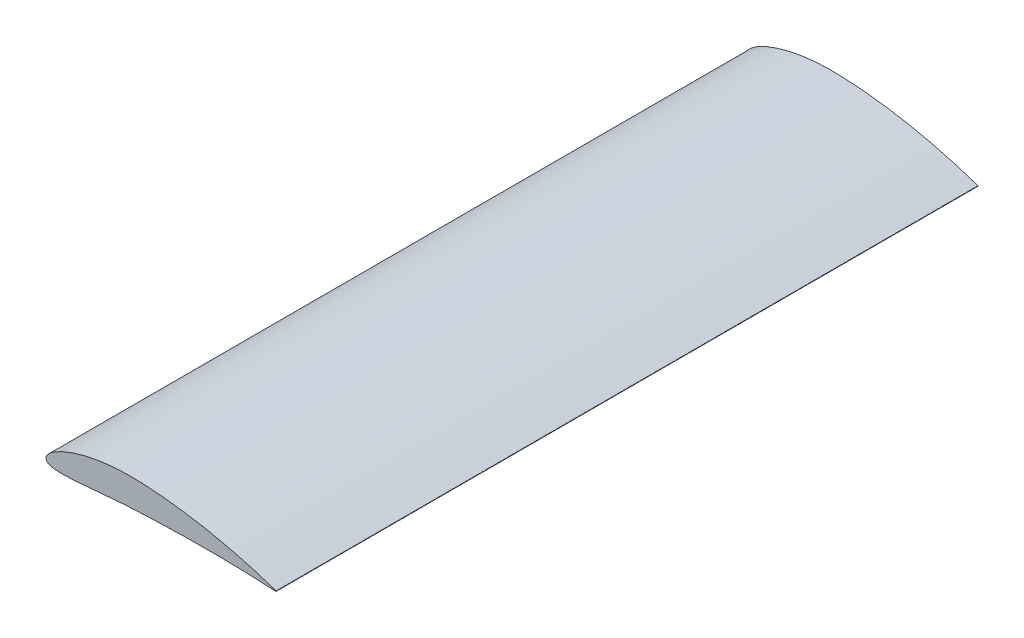
SolidWorks part; units mm, degrees
ref_plane "Front Plane" through (0, 0, 0) normal (0, 0, 1) x (1, 0, 0)
ref_plane "Top Plane" through (0, 0, 0) normal (0, 1, 0) x (1, 0, 0)
ref_plane "Right Plane" through (0, 0, 0) normal (1, 0, 0) x (0, 0, -1)
curve "Curve1"
  spline degree 3 poles (25.4063, 0.0315, 0) (25.3837, 0.0393, 0) (25.2937, 0.0703, 0) (25.0921, 0.1399, 0) (24.7577, 0.2522, 0) (24.2942, 0.405, 0) (23.7055, 0.5921, 0) (22.997, 0.8077, 0) (22.1758, 1.0451, 0) (21.2496, 1.2966, 0) (20.228, 1.5548, 0) (19.121, 1.8116, 0) (17.9406, 2.0603, 0) (16.6991, 2.2931, 0) (15.4099, 2.5029, 0) (14.087, 2.6845, 0) (12.7455, 2.832, 0) (11.3997, 2.9406, 0) (10.0556, 3.012, 0) (8.7276, 3.0204, 0) (7.4344, 2.9555, 0) (6.2027, 2.8238, 0) (5.0487, 2.6331, 0) (3.9878, 2.3917, 0) (3.0332, 2.1114, 0) (2.1961, 1.8047, 0) (1.4854, 1.4841, 0) (0.9079, 1.1619, 0) (0.4662, 0.8495, 0) (0.1626, 0.5537, 0) (-0.0122, 0.2735, 0) (-0.028, -0.0084, 0) (0.1391, -0.2343, 0) (0.4322, -0.3758, 0) (0.835, -0.4687, 0) (1.354, -0.5173, 0) (1.984, -0.5271, 0) (2.719, -0.502, 0) (3.5507, -0.4482, 0) (4.4705, -0.3722, 0) (5.4695, -0.2826, 0) (6.5387, -0.187, 0) (7.6688, -0.0938, 0) (8.8505, -0.0116, 0) (10.0833, 0.0504, 0) (11.3564, 0.0941, 0) (12.6563, 0.1392, 0) (13.9604, 0.1753, 0) (15.2542, 0.2014, 0) (16.5239, 0.216, 0) (17.7555, 0.2186, 0) (18.9353, 0.21, 0) (20.05, 0.192, 0) (21.0867, 0.1653, 0) (22.0333, 0.1345, 0) (22.8789, 0.1002, 0) (23.6118, 0.0674, 0) (24.228, 0.0327, 0) (24.706, 0.0159, 0) (25.0741, -0.0269, 0) (25.2565, -0.0004, 0) (25.3969, -0.052, 0) (25.3993, -0.0123, 0) (25.4, 0, 0) knots 0 0 0 0 0.001372 0.005465 0.012235 0.021602 0.033461 0.047671 0.064081 0.082496 0.102719 0.124527 0.147676 0.171913 0.196978 0.222597 0.248497 0.274385 0.300041 0.32569 0.350525 0.37428 0.396711 0.417577 0.436654 0.453744 0.46868 0.481329 0.491631 0.499616 0.505546 0.510185 0.514824 0.520702 0.528516 0.538466 0.550543 0.564643 0.580638 0.598345 0.617584 0.638174 0.659922 0.682632 0.706121 0.730727 0.7557 0.780732 0.805564 0.829932 0.85357 0.876213 0.89761 0.917519 0.935698 0.951943 0.966047 0.97784 0.987174 0.993932 0.998018 0.999386 1 1 1 1
ref_plane "Ground" through (0, 50, 0) normal (0, 1, 0) x (1, 0, 0)
sketch "Sketch1" plane through (0, 0, 0) normal (0, 0, 1) x (1, 0, 0)
  line L0 (399.9016, -56.6273) -> (400, -56.1315)
  line L1 (400, -56.1315) -> (0, -56.1315) construction
  line L2 (0, -56.1315) -> (0, -58.6766) construction
  line L3 (0, -56.1315) -> (33.1119, -56.1315) construction
  line L4 (0, 50) -> (0, -115.3886) construction
  line L5 (244.1729, 50) -> (-244.1729, 50) construction
  line L6 (120.4, -56.1315) -> (116.5924, -10) construction
  line L7 (-44.4989, -10) -> (307.508, -10) construction
  spline S1 degree 3 poles (400, -56.1315) (399.6439, -56.01) (398.2252, -55.5262) (395.0494, -54.4413) (389.7834, -52.6913) (382.4827, -50.3092) (373.21, -47.3936) (362.0519, -44.0359) (349.1184, -40.342) (334.534, -36.4293) (318.4458, -32.4165) (301.0159, -28.4316) (282.4307, -24.5755) (262.8848, -20.9743) (242.5889, -17.7351) (221.7662, -14.9428) (200.6508, -12.6886) (179.4693, -11.0453) (158.3174, -9.9888) (137.4224, -9.9218) (117.0768, -11.0062) (97.7026, -13.1385) (79.5557, -16.1958) (62.8746, -20.0462) (47.8681, -24.5037) (34.711, -29.37) (23.5446, -34.4495) (14.474, -39.5475) (7.5391, -44.4847) (2.7768, -49.154) (0.0409, -53.5706) (-0.1945, -58.008) (2.4464, -61.5541) (7.0638, -63.7654) (13.4071, -65.2069) (21.576, -65.9474) (31.4893, -66.0698) (43.0523, -65.6389) (56.1353, -64.7525) (70.6041, -63.511) (86.3185, -62.0516) (103.1371, -60.4954) (120.9147, -58.9731) (139.5039, -57.6216) (158.8992, -56.5864) (178.9277, -55.8354) (199.3786, -55.0619) (219.8967, -54.4309) (240.2531, -53.9568) (260.2306, -53.6642) (279.6093, -53.5627) (298.1732, -53.6409) (315.7128, -53.8686) (332.026, -54.2377) (346.9212, -54.6757) (360.2284, -55.1752) (371.7614, -55.6544) (381.4587, -56.1708) (388.9808, -56.412) (394.7752, -57.0663) (397.6444, -56.6402) (399.8562, -57.446) (399.8909, -56.8211) (399.9016, -56.6273) knots 0 0 0 0 0.001372 0.005465 0.012235 0.021602 0.033461 0.047671 0.064081 0.082496 0.102719 0.124527 0.147676 0.171913 0.196978 0.222597 0.248497 0.274385 0.300041 0.32569 0.350525 0.37428 0.396711 0.417577 0.436654 0.453744 0.46868 0.481329 0.491631 0.499616 0.505546 0.510185 0.514824 0.520702 0.528516 0.538466 0.550543 0.564643 0.580638 0.598345 0.617584 0.638174 0.659922 0.682632 0.706121 0.730727 0.7557 0.780732 0.805564 0.829932 0.85357 0.876213 0.89761 0.917519 0.935698 0.951943 0.966047 0.97784 0.987174 0.993932 0.998018 0.999386 1 1 1 1
  point P2 (120.4, -56.1315)
  dimension "D1" = 400
  dimension "D2" = 0
  dimension "D4" = 120.4
  dimension "D3" = 10
ref_plane "Plane2" through (0, 0, 75) normal (0, 0, 1) x (1, 0, 0)
ref_plane "Plane3" through (0, 0, 405) normal (0, 0, 1) x (1, 0, 0)
ref_plane "Plane4" through (0, 0, 680) normal (0, 0, 1) x (1, 0, 0)
sketch "Sketch3" plane through (0, 0, 75) normal (0, 0, 1) x (1, 0, 0)
  line L0 (399.9016, -56.6273) -> (400, -56.1315) construction
  line L1 (399.9016, -56.6273) -> (400, -56.1315)
  spline S0 degree 3 poles (385.3519, -1055.9885) (590.8884, -117.467) (493.2691, -87.9956) (395.0494, -54.4413) (389.7834, -52.6913) (382.4827, -50.3092) (373.21, -47.3936) (362.0519, -44.0359) (349.1184, -40.342) (334.534, -36.4293) (318.4458, -32.4165) (301.0159, -28.4316) (282.4307, -24.5755) (262.8848, -20.9743) (242.5889, -17.7351) (221.7662, -14.9428) (200.6508, -12.6886) (179.4693, -11.0453) (158.3174, -9.9888) (137.4224, -9.9218) (117.0768, -11.0062) (97.7026, -13.1385) (79.5557, -16.1958) (62.8746, -20.0462) (47.8681, -24.5037) (34.711, -29.37) (23.5446, -34.4495) (14.474, -39.5475) (7.5391, -44.4847) (2.7768, -49.154) (0.0409, -53.5706) (-0.1945, -58.008) (2.4464, -61.5541) (7.0638, -63.7654) (13.4071, -65.2069) (21.576, -65.9474) (31.4893, -66.0698) (43.0523, -65.6389) (56.1353, -64.7525) (70.6041, -63.511) (86.3185, -62.0516) (103.1371, -60.4954) (120.9147, -58.9731) (139.5039, -57.6216) (158.8992, -56.5864) (178.9277, -55.8354) (199.3786, -55.0619) (219.8967, -54.4309) (240.2531, -53.9568) (260.2306, -53.6642) (279.6093, -53.5627) (298.1732, -53.6409) (315.7128, -53.8686) (332.026, -54.2377) (346.9212, -54.6757) (360.2284, -55.1752) (371.7614, -55.6544) (381.4587, -56.1708) (388.9808, -56.412) (394.7752, -57.0663) (397.6444, -56.6402) (404.5727, -59.1646) (371.0225, -10.7821) (1018.233, -842.2365) knots -0.366161 -0.366161 -0.366161 -0.366161 0.001372 0.005465 0.012235 0.021602 0.033461 0.047671 0.064081 0.082496 0.102719 0.124527 0.147676 0.171913 0.196978 0.222597 0.248497 0.274385 0.300041 0.32569 0.350525 0.37428 0.396711 0.417577 0.436654 0.453744 0.46868 0.481329 0.491631 0.499616 0.505546 0.510185 0.514824 0.520702 0.528516 0.538466 0.550543 0.564643 0.580638 0.598345 0.617584 0.638174 0.659922 0.682632 0.706121 0.730727 0.7557 0.780732 0.805564 0.829932 0.85357 0.876213 0.89761 0.917519 0.935698 0.951943 0.966047 0.97784 0.987174 0.993932 0.998018 0.999386 1.012941 1.012941 1.012941 1.012941 only from (400, -56.1315) to (399.9016, -56.6273) construction
  spline S1 degree 3 poles (400, -56.1315) (399.6439, -56.01) (398.2252, -55.5262) (395.0494, -54.4413) (389.7834, -52.6913) (382.4827, -50.3092) (373.21, -47.3936) (362.0519, -44.0359) (349.1184, -40.342) (334.534, -36.4293) (318.4458, -32.4165) (301.0159, -28.4316) (282.4307, -24.5755) (262.8848, -20.9743) (242.5889, -17.7351) (221.7662, -14.9428) (200.6508, -12.6886) (179.4693, -11.0453) (158.3174, -9.9888) (137.4224, -9.9218) (117.0768, -11.0062) (97.7026, -13.1385) (79.5557, -16.1958) (62.8746, -20.0462) (47.8681, -24.5037) (34.711, -29.37) (23.5446, -34.4495) (14.474, -39.5475) (7.5391, -44.4847) (2.7768, -49.154) (0.0409, -53.5706) (-0.1945, -58.008) (2.4464, -61.5541) (7.0638, -63.7654) (13.4071, -65.2069) (21.576, -65.9474) (31.4893, -66.0698) (43.0523, -65.6389) (56.1353, -64.7525) (70.6041, -63.511) (86.3185, -62.0516) (103.1371, -60.4954) (120.9147, -58.9731) (139.5039, -57.6216) (158.8992, -56.5864) (178.9277, -55.8354) (199.3786, -55.0619) (219.8967, -54.4309) (240.2531, -53.9568) (260.2306, -53.6642) (279.6093, -53.5627) (298.1732, -53.6409) (315.7128, -53.8686) (332.026, -54.2377) (346.9212, -54.6757) (360.2284, -55.1752) (371.7614, -55.6544) (381.4587, -56.1708) (388.9808, -56.412) (394.7752, -57.0663) (397.6444, -56.6402) (399.8562, -57.446) (399.8909, -56.8211) (399.9016, -56.6273) knots 0 0 0 0 0.001372 0.005465 0.012235 0.021602 0.033461 0.047671 0.064081 0.082496 0.102719 0.124527 0.147676 0.171913 0.196978 0.222597 0.248497 0.274385 0.300041 0.32569 0.350525 0.37428 0.396711 0.417577 0.436654 0.453744 0.46868 0.481329 0.491631 0.499616 0.505546 0.510185 0.514824 0.520702 0.528516 0.538466 0.550543 0.564643 0.580638 0.598345 0.617584 0.638174 0.659922 0.682632 0.706121 0.730727 0.7557 0.780732 0.805564 0.829932 0.85357 0.876213 0.89761 0.917519 0.935698 0.951943 0.966047 0.97784 0.987174 0.993932 0.998018 0.999386 1 1 1 1
  point P2 (0, 0)
sketch "Sketch4" plane through (0, 0, 405) normal (0, 0, 1) x (1, 0, 0)
  line L0 (295.4423, -52.0945) -> (0, 0) construction
  line L1 (295.3051, -52.4479) -> (295.4423, -52.0945)
  line L2 (0, 0) -> (21.2699, 120.6274) construction
  line L3 (0, 0) -> (22.2171, 0) construction
  spline S1 degree 3 poles (295.4423, -52.0945) (295.1951, -51.9584) (294.2103, -51.4162) (292.0059, -50.2013) (288.3443, -48.2229) (283.2622, -45.5127) (276.793, -42.1516) (268.989, -38.2184) (259.9173, -33.8057) (249.6547, -29.0163) (238.2945, -23.9571) (225.9396, -18.7439) (212.7147, -13.4753) (198.7469, -8.2698) (184.1782, -3.234) (169.1621, 1.5402) (153.8597, 5.9552) (138.4289, 9.9275) (122.9436, 13.4626) (107.5192, 16.2333) (92.3506, 18.0821) (77.7629, 19.0304) (63.9613, 19.1357) (51.1392, 18.4643) (39.4747, 17.1263) (29.1231, 15.2455) (20.2139, 12.948) (12.8504, 10.364) (7.0853, 7.6205) (2.9597, 4.792) (0.3637, 1.8861) (-0.3881, -1.3607) (1.1007, -4.3238) (4.2232, -6.5585) (8.7206, -8.4493) (14.6577, -10.0601) (21.9638, -11.4415) (30.5605, -12.6292) (40.3391, -13.6784) (51.1875, -14.6458) (62.9843, -15.6144) (75.6093, -16.6554) (88.9382, -17.8463) (102.8443, -19.2691) (117.3046, -21.0304) (132.1956, -23.0842) (147.4015, -25.1763) (162.6385, -27.3824) (177.7355, -29.6834) (192.5291, -32.0691) (206.8556, -34.5179) (220.5568, -36.9934) (233.482, -39.4458) (245.483, -41.843) (256.4276, -44.1064) (266.1913, -46.2084) (274.6473, -48.0644) (281.7425, -49.7088) (287.2669, -50.8666) (291.4615, -52.1045) (293.6362, -52.1634) (295.1649, -53.0467) (295.2719, -52.5896) (295.3051, -52.4479) knots 0 0 0 0 0.001372 0.005465 0.012235 0.021602 0.033461 0.047671 0.064081 0.082496 0.102719 0.124527 0.147676 0.171913 0.196978 0.222597 0.248497 0.274385 0.300041 0.32569 0.350525 0.37428 0.396711 0.417577 0.436654 0.453744 0.46868 0.481329 0.491631 0.499616 0.505546 0.510185 0.514824 0.520702 0.528516 0.538466 0.550543 0.564643 0.580638 0.598345 0.617584 0.638174 0.659922 0.682632 0.706121 0.730727 0.7557 0.780732 0.805564 0.829932 0.85357 0.876213 0.89761 0.917519 0.935698 0.951943 0.966047 0.97784 0.987174 0.993932 0.998018 0.999386 1 1 1 1
  dimension "D1" = 10
  dimension "D2" = 300
sketch "Sketch6" plane through (0, 0, 680) normal (0, 0, 1) x (1, 0, 0)
  line L0 (299.7305, -10.839) -> (299.8172, -10.4698)
  line L1 (299.8172, -10.4698) -> (0, 0) construction
  line L2 (0, 0) -> (0.2404, 6.883) construction
  line L3 (0, 0) -> (23.729, 0) construction
  spline S1 degree 3 poles (299.8172, -10.4698) (299.5535, -10.3695) (298.5028, -9.9697) (296.1508, -9.0734) (292.2495, -7.6239) (286.8397, -5.6473) (279.9657, -3.2192) (271.6901, -0.4104) (262.0926, 2.6968) (251.2634, 6.0113) (239.3096, 9.4402) (226.3494, 12.8832) (212.52, 16.26) (197.9637, 19.4709) (182.8359, 22.4301) (167.3014, 25.068) (151.5335, 27.3103) (135.7001, 29.0964) (119.8735, 30.442) (104.2135, 31.0391) (88.9353, 30.7589) (74.3576, 29.6677) (60.6757, 27.8512) (48.0718, 25.4018) (36.707, 22.4535) (26.7179, 19.1503) (18.2152, 15.6353) (11.283, 12.0515) (5.9557, 8.5324) (2.264, 5.1572) (0.0977, 1.9184) (-0.1949, -1.4014) (1.6918, -4.1286) (5.0948, -5.9069) (9.8117, -7.1534) (15.9152, -7.9222) (23.3424, -8.2734) (32.0207, -8.2531) (41.8502, -7.9312) (52.7277, -7.3793) (64.5445, -6.6968) (77.1915, -5.9705) (90.5564, -5.2948) (104.5252, -4.7684) (119.0899, -4.5001) (134.1218, -4.4615) (149.4709, -4.417) (164.8666, -4.4811) (180.1369, -4.6585) (195.1186, -4.9621) (209.6465, -5.3933) (223.5588, -5.9378) (236.6996, -6.5675) (248.9174, -7.2712) (260.0705, -7.9894) (270.0318, -8.7121) (278.6637, -9.3732) (285.9187, -10.014) (291.5505, -10.3917) (295.8766, -11.0338) (298.0383, -10.7895) (299.675, -11.4514) (299.7174, -10.9839) (299.7305, -10.839) knots 0 0 0 0 0.001372 0.005465 0.012235 0.021602 0.033461 0.047671 0.064081 0.082496 0.102719 0.124527 0.147676 0.171913 0.196978 0.222597 0.248497 0.274385 0.300041 0.32569 0.350525 0.37428 0.396711 0.417577 0.436654 0.453744 0.46868 0.481329 0.491631 0.499616 0.505546 0.510185 0.514824 0.520702 0.528516 0.538466 0.550543 0.564643 0.580638 0.598345 0.617584 0.638174 0.659922 0.682632 0.706121 0.730727 0.7557 0.780732 0.805564 0.829932 0.85357 0.876213 0.89761 0.917519 0.935698 0.951943 0.966047 0.97784 0.987174 0.993932 0.998018 0.999386 1 1 1 1
  dimension "D1" = 2
  dimension "D2" = 300
ref_plane "Plane5" through (0, 0, 590) normal (0, 0, 1) x (1, 0, 0)
sketch "Sketch7" plane through (0, 0, 590) normal (0, 0, 1) x (1, 0, 0)
  line L0 (299.7305, -10.839) -> (299.8172, -10.4698) construction
  line L1 (299.7305, -10.839) -> (299.8172, -10.4698)
  spline S0 degree 3 poles (-87.8025, -1963.6829) (498.7146, -80.5328) (397.1503, -47.5635) (296.1508, -9.0734) (292.2495, -7.6239) (286.8397, -5.6473) (279.9657, -3.2192) (271.6901, -0.4104) (262.0926, 2.6968) (251.2634, 6.0113) (239.3096, 9.4402) (226.3494, 12.8832) (212.52, 16.26) (197.9637, 19.4709) (182.8359, 22.4301) (167.3014, 25.068) (151.5335, 27.3103) (135.7001, 29.0964) (119.8735, 30.442) (104.2135, 31.0391) (88.9353, 30.7589) (74.3576, 29.6677) (60.6757, 27.8512) (48.0718, 25.4018) (36.707, 22.4535) (26.7179, 19.1503) (18.2152, 15.6353) (11.283, 12.0515) (5.9557, 8.5324) (2.264, 5.1572) (0.0977, 1.9184) (-0.1949, -1.4014) (1.6918, -4.1286) (5.0948, -5.9069) (9.8117, -7.1534) (15.9152, -7.9222) (23.3424, -8.2734) (32.0207, -8.2531) (41.8502, -7.9312) (52.7277, -7.3793) (64.5445, -6.6968) (77.1915, -5.9705) (90.5564, -5.2948) (104.5252, -4.7684) (119.0899, -4.5001) (134.1218, -4.4615) (149.4709, -4.417) (164.8666, -4.4811) (180.1369, -4.6585) (195.1186, -4.9621) (209.6465, -5.3933) (223.5588, -5.9378) (236.6996, -6.5675) (248.9174, -7.2712) (260.0705, -7.9894) (270.0318, -8.7121) (278.6637, -9.3732) (285.9187, -10.014) (291.5505, -10.3917) (295.8766, -11.0338) (298.0383, -10.7895) (304.5078, -13.4059) (260.2474, 53.3734) (1474.4582, -1628.662) knots -0.513155 -0.513155 -0.513155 -0.513155 0.001372 0.005465 0.012235 0.021602 0.033461 0.047671 0.064081 0.082496 0.102719 0.124527 0.147676 0.171913 0.196978 0.222597 0.248497 0.274385 0.300041 0.32569 0.350525 0.37428 0.396711 0.417577 0.436654 0.453744 0.46868 0.481329 0.491631 0.499616 0.505546 0.510185 0.514824 0.520702 0.528516 0.538466 0.550543 0.564643 0.580638 0.598345 0.617584 0.638174 0.659922 0.682632 0.706121 0.730727 0.7557 0.780732 0.805564 0.829932 0.85357 0.876213 0.89761 0.917519 0.935698 0.951943 0.966047 0.97784 0.987174 0.993932 0.998018 0.999386 1.017919 1.017919 1.017919 1.017919 only from (299.8172, -10.4698) to (299.7305, -10.839) construction
  spline S1 degree 3 poles (299.8172, -10.4698) (299.5535, -10.3695) (298.5028, -9.9697) (296.1508, -9.0734) (292.2495, -7.6239) (286.8397, -5.6473) (279.9657, -3.2192) (271.6901, -0.4104) (262.0926, 2.6968) (251.2634, 6.0113) (239.3096, 9.4402) (226.3494, 12.8832) (212.52, 16.26) (197.9637, 19.4709) (182.8359, 22.4301) (167.3014, 25.068) (151.5335, 27.3103) (135.7001, 29.0964) (119.8735, 30.442) (104.2135, 31.0391) (88.9353, 30.7589) (74.3576, 29.6677) (60.6757, 27.8512) (48.0718, 25.4018) (36.707, 22.4535) (26.7179, 19.1503) (18.2152, 15.6353) (11.283, 12.0515) (5.9557, 8.5324) (2.264, 5.1572) (0.0977, 1.9184) (-0.1949, -1.4014) (1.6918, -4.1286) (5.0948, -5.9069) (9.8117, -7.1534) (15.9152, -7.9222) (23.3424, -8.2734) (32.0207, -8.2531) (41.8502, -7.9312) (52.7277, -7.3793) (64.5445, -6.6968) (77.1915, -5.9705) (90.5564, -5.2948) (104.5252, -4.7684) (119.0899, -4.5001) (134.1218, -4.4615) (149.4709, -4.417) (164.8666, -4.4811) (180.1369, -4.6585) (195.1186, -4.9621) (209.6465, -5.3933) (223.5588, -5.9378) (236.6996, -6.5675) (248.9174, -7.2712) (260.0705, -7.9894) (270.0318, -8.7121) (278.6637, -9.3732) (285.9187, -10.014) (291.5505, -10.3917) (295.8766, -11.0338) (298.0383, -10.7895) (299.675, -11.4514) (299.7174, -10.9839) (299.7305, -10.839) knots 0 0 0 0 0.001372 0.005465 0.012235 0.021602 0.033461 0.047671 0.064081 0.082496 0.102719 0.124527 0.147676 0.171913 0.196978 0.222597 0.248497 0.274385 0.300041 0.32569 0.350525 0.37428 0.396711 0.417577 0.436654 0.453744 0.46868 0.481329 0.491631 0.499616 0.505546 0.510185 0.514824 0.520702 0.528516 0.538466 0.550543 0.564643 0.580638 0.598345 0.617584 0.638174 0.659922 0.682632 0.706121 0.730727 0.7557 0.780732 0.805564 0.829932 0.85357 0.876213 0.89761 0.917519 0.935698 0.951943 0.966047 0.97784 0.987174 0.993932 0.998018 0.999386 1 1 1 1
  point P2 (0, 0)
extrude "Boss-Extrude1" add sketch "Sketch1" along normal mid plane 1220 contours S1 L0
equation "\"Cord Outboard\"=400"
equation "\"D1@Sketch1\"=\"Cord Outboard\""
equation "\"AoA OutBoard\"=0"
equation "\"D2@Sketch1\"=\"AoA OutBoard\""
equation "\"Outboard Width\"= 75"
equation "\"D1@Plane2\"=\"Outboard Width\""
equation "\"Midplane Width\"= 330"
equation "\"D1@Plane3\"=\"Midplane Width\""
equation "\"Total Width\"= 1360 / 2"
equation "\"Inboard Width1\"= \"Total Width\" - \"Outboard Width\" - \"Midplane Width\""
equation "\"AoA Mid Plane\"= 10"
equation "\"Cord MidPlane\"= 300"
equation "\"AoA Inboard\"= 2"
equation "\"Cord Inboard\"= 300"
equation "\"Inboard Width2\"= 120"
